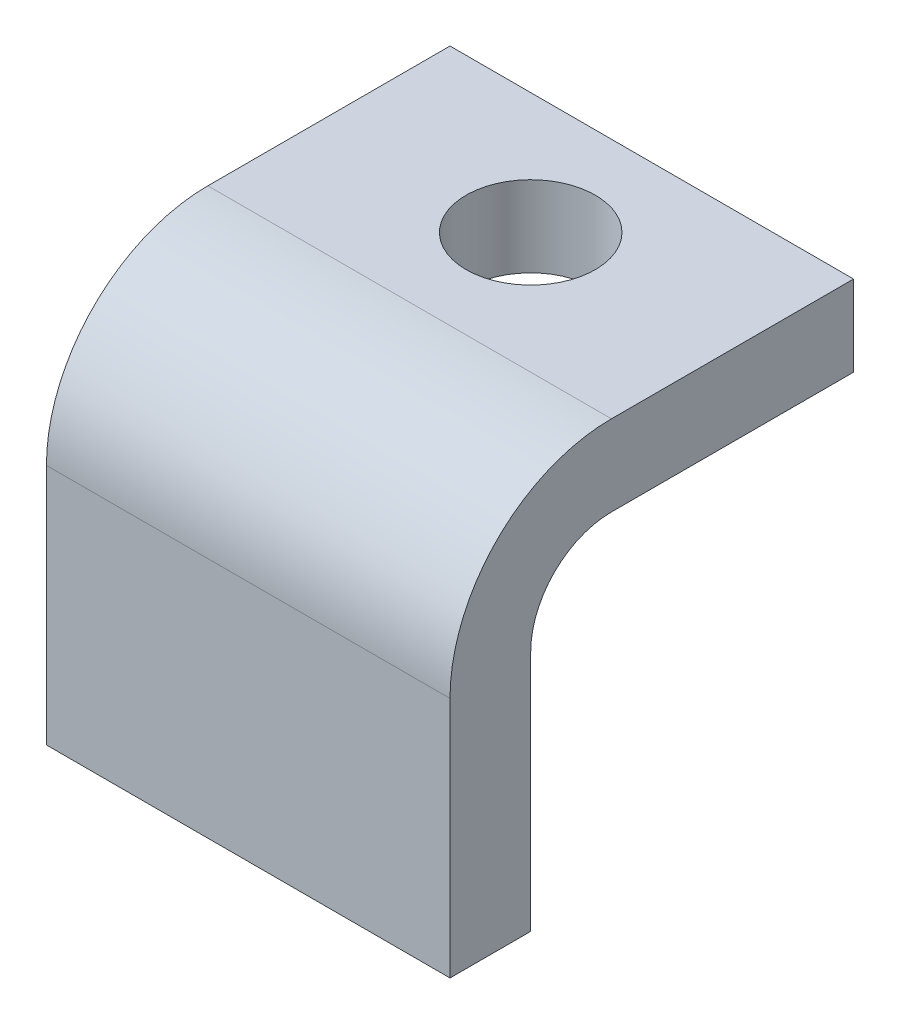
SolidWorks part; units mm, degrees
material "延性铁"
ref_plane "前视基准面" through (0, 0, 0) normal (0, 0, 1) x (1, 0, 0)
ref_plane "上视基准面" through (0, 0, 0) normal (0, 1, 0) x (1, 0, 0)
ref_plane "右视基准面" through (0, 0, 0) normal (1, 0, 0) x (0, 0, -1)
sketch "草图1" plane through (0, 0, 0) normal (1, 0, 0) x (0, 0, -1)
  line L0 (0, 0) -> (0, 10)
  line L1 (0, 10) -> (10, 10)
  dimension "D1" = 10
  dimension "D2" = 10
extrude "拉伸-薄壁1" add sketch "草图1" along normal mid plane 10 thin
hole_wizard "M3 间隙孔1" positions "草图3" profile "草图2" hole size "M3" standard "GB" end condition up to next
sketch "草图3" plane through (0, 10, 0) normal (0, 1, 0) x (1, 0, 0)
  line L0 (5, 10) -> (-5, 10) construction
  point P0 (0, 7)
  dimension "D1" = 3
sketch "草图2" plane through (0, 10, -7) normal (1, 0, 0) x (0, 0, 1)
  line L0 (0, 0) -> (0, 2)
  line L1 (0, 2) -> (1.6, 2)
  line L2 (1.6, 2) -> (1.6, 0)
  line L5 (1.6, 0) -> (0, 0)
  line L11 (0, -6.35) -> (0, 107.95) construction
  dimension "通孔孔直径" = 3.2
  dimension "通孔孔深度" = 2
